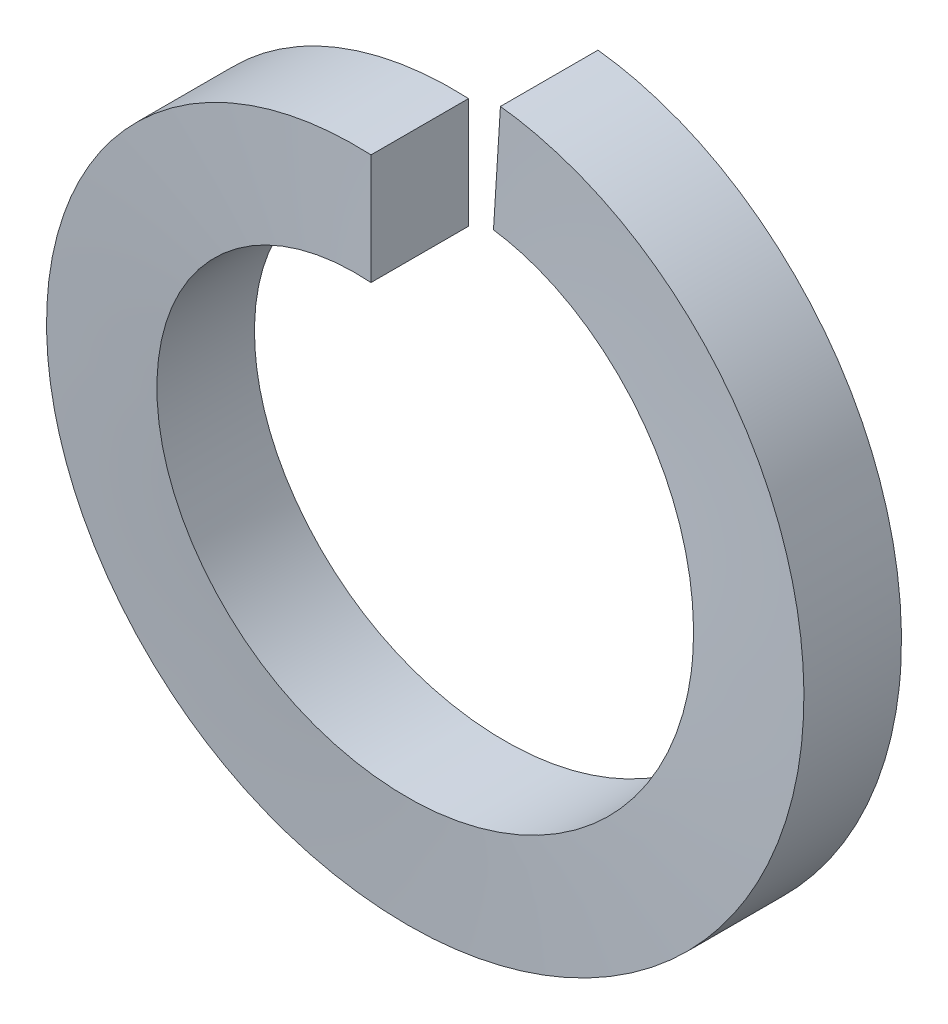
SolidWorks part; units mm, degrees
ref_plane "Front Plane" through (0, 0, 0) normal (0, 0, 1) x (1, 0, 0)
ref_plane "Top Plane" through (0, 0, 0) normal (0, 1, 0) x (1, 0, 0)
ref_plane "Right Plane" through (0, 0, 0) normal (1, 0, 0) x (0, 0, -1)
sketch "Sketch1" plane through (0, 0, 0) normal (0, 0, 1) x (1, 0, 0)
  line L0 (0, 2.7432) -> (0, 1.8796) construction
  circle A0 centre (0, 0) radius 2.7432
  circle A1 centre (0, 0) radius 1.8796 construction
  dimension "ID" = 3.7592
  dimension "OD" = 5.4864
curve "Helix/Spiral1" pitch 0.8467 height 0.8382 turns 0.99 parameters "HT"=0.8382
sketch "Sketch2" plane through (0, 0, 0) normal (1, 0, 0) x (0, 0, -1)
  line L1 (0, 2.7432) -> (-0.762, 2.7432)
  line L2 (0, 2.7432) -> (0, 1.8796)
  line L3 (0, 1.8796) -> (-0.762, 1.8796)
  line L4 (-0.762, 2.7432) -> (-0.762, 1.8796)
  dimension "THK" = 0.762
sweep "Sweep1" add profiles "Sketch2" path "Helix/Spiral1"
equation "\"HT@Helix/Spiral1\" = \"THK@Sketch2\"*1.1"
